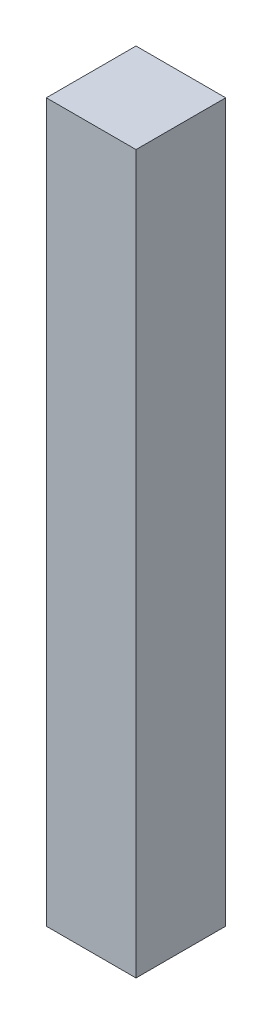
SolidWorks part; units mm, degrees
material "混合材料"
ref_plane "前视基准面" through (0, 0, 0) normal (0, 0, 1) x (1, 0, 0)
ref_plane "上视基准面" through (0, 0, 0) normal (0, 1, 0) x (1, 0, 0)
ref_plane "右视基准面" through (0, 0, 0) normal (1, 0, 0) x (0, 0, -1)
sketch "草图1" plane through (0, 0, 0) normal (0, 0, 1) x (1, 0, 0)
  line L1 (-25, -200) -> (25, -200)
  line L2 (-25, -200) -> (-25, 200)
  line L3 (-25, 200) -> (25, 200)
  line L4 (25, -200) -> (25, 200)
  line L5 (-25, -200) -> (25, 200) construction
  line L6 (-25, 200) -> (25, -200) construction
  point P0 (0, 0)
  dimension "D1" = 400
  dimension "D2" = 50
extrude "凸台-拉伸1" add sketch "草图1" along normal blind 50
